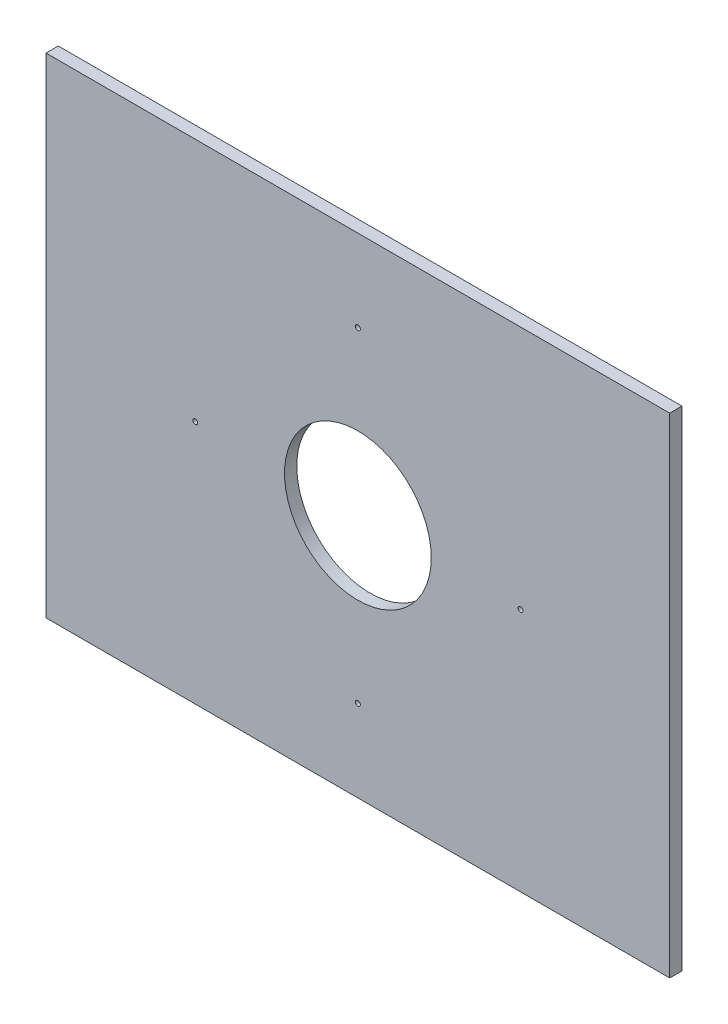
SolidWorks part; units mm, degrees
ref_plane "Front Plane" through (0, 0, 0) normal (0, 0, 1) x (1, 0, 0)
ref_plane "Top Plane" through (0, 0, 0) normal (0, 1, 0) x (1, 0, 0)
ref_plane "Right Plane" through (0, 0, 0) normal (1, 0, 0) x (0, 0, -1)
sketch "Sketch1" plane through (0, 0, 0) normal (0, 0, 1) x (1, 0, 0)
  line L0 (0, 200) -> (255, 0) construction
  line L1 (0, 0) -> (255, 0)
  line L2 (0, 0) -> (0, 200)
  line L3 (0, 200) -> (255, 200)
  line L4 (255, 0) -> (255, 200)
  line L5 (0, 0) -> (255, 200) construction
  line L6 (127.5, 100) -> (0, 100) construction
  line L7 (0, 100) -> (255, 100) construction
  circle A0 centre (127.5, 100) radius 30
  point P20 (127.5, 100)
  dimension "D3" = 60
  dimension "D1" = 255
  dimension "D2" = 200
  dimension "D6" = 0
extrude "Boss-Extrude1" add sketch "Sketch1" along normal blind 5
sketch "Sketch2" plane through (0, 0, 0) normal (0, 0, 1) x (1, 0, 0)
  line L0 (0, 100) -> (255, 100) construction
  line L1 (0, 200) -> (0, 0) construction
  line L2 (255, 0) -> (255, 200) construction
  line L3 (255, 100) -> (127.5, 200) construction
  line L4 (255, 200) -> (0, 200) construction
  line L5 (127.5, 200) -> (127.5, 0) construction
  line L6 (0, 0) -> (255, 0) construction
  line L7 (127.5, 227.5) -> (127.5, -27.5) construction
  line L8 (255, 100) -> (0, 100) construction
  line L9 (127.5, -27.5) -> (127.5, 227.5) construction
  circle A0 centre (61, 100) radius 1
  circle A1 centre (127.5, 166.5) radius 1
  circle A2 centre (194, 100) radius 1
  circle A3 centre (127.5, 33.5) radius 1
  point P29 (127.5, 100)
  dimension "D1" = 2
  dimension "D2" = 66.5
  dimension "D3" = 4
extrude "Cut-Extrude1" cut sketch "Sketch2" along normal blind 28
